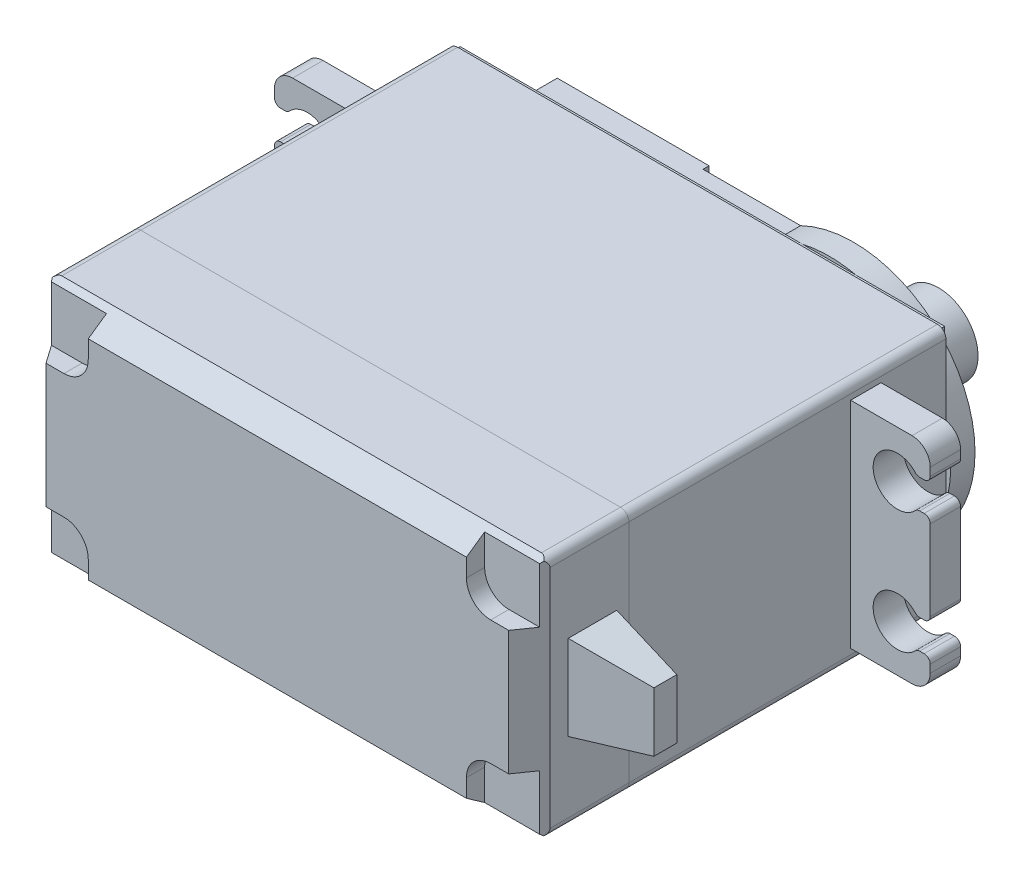
SolidWorks part; units mm, degrees
ref_plane "Front Plane" through (0, 0, 0) normal (0, 0, 1) x (1, 0, 0)
ref_plane "Top Plane" through (0, 0, 0) normal (0, 1, 0) x (1, 0, 0)
ref_plane "Right Plane" through (0, 0, 0) normal (1, 0, 0) x (0, 0, -1)
sketch "Sketch1" plane through (0, 0, 0) normal (0, 0, 1) x (1, 0, 0)
  line L1 (20.45, -10) -> (-20.45, -10)
  line L2 (20.45, -10) -> (20.45, 10)
  line L3 (20.45, 10) -> (-20.45, 10)
  line L4 (-20.45, -10) -> (-20.45, 10)
  line L5 (20.45, -10) -> (-20.45, 10) construction
  line L6 (20.45, 10) -> (-20.45, -10) construction
  point P0 (0, 0)
  dimension "D1" = 40.9
  dimension "D2" = 20
extrude "Boss-Extrude1" add sketch "Sketch1" along normal blind 19.3
sketch "Sketch3" plane through (0, 0, 0) normal (0, 0, -1) x (-1, 0, 0)
  line L4 (20.45, -10) -> (20.45, 10)
  line L5 (20.45, 10) -> (-20.45, 10)
  line L6 (-20.45, 10) -> (-20.45, -10)
  line L7 (-20.45, -10) -> (20.45, -10)
  line L8 (20.45, -10) -> (20.45, 10)
  line L9 (20.45, 10) -> (-20.45, 10)
  line L10 (-20.45, 10) -> (-20.45, -10)
  line L11 (-20.45, -10) -> (20.45, -10)
  dimension "D1" = 0
extrude "Boss-Extrude2" add sketch "Sketch3" along normal blind 6.8 separate body
sketch "Sketch4" plane through (0, 0, 19.3) normal (0, 0, 1) x (1, 0, 0)
  line L4 (-20.45, 10) -> (-20.45, -10)
  line L5 (-20.45, -10) -> (20.45, -10)
  line L6 (20.45, -10) -> (20.45, 10)
  line L7 (20.45, 10) -> (-20.45, 10)
  line L8 (-20.45, 10) -> (-20.45, -10)
  line L9 (-20.45, -10) -> (20.45, -10)
  line L10 (20.45, -10) -> (20.45, 10)
  line L11 (20.45, 10) -> (-20.45, 10)
  dimension "D1" = 0
extrude "Boss-Extrude3" add sketch "Sketch4" along normal blind 8.5 separate body
chamfer "Chamfer1" distance 2 angle 35 4 edges at (20.45, 0, 27.8) (0, -10, 27.8) (-20.45, 0, 27.8) (0, 10, 27.8)
sketch "Sketch5" plane through (0, 0, 27.8) normal (0, 0, 1) x (1, 0, 0)
  line L0 (-20.45, 10) -> (-19.0496, 8.5996) construction
  line L1 (-20.45, 10) -> (-15.57, 10)
  line L2 (-20.45, 10) -> (-20.45, 5.12)
  line L3 (-20.45, 5.12) -> (-17.57, 5.12)
  line L4 (-15.57, 10) -> (-15.57, 7.12)
  line L5 (-20.45, 10) -> (20.45, 10) construction
  line L6 (0, 10) -> (0, -11.6443) construction
  line L7 (0, 0) -> (20.45, 0) construction
  line L8 (20.45, 10) -> (20.45, -10) construction
  line L9 (20.45, 5.12) -> (17.57, 5.12)
  line L10 (15.57, 10) -> (15.57, 7.12)
  line L11 (20.45, 10) -> (15.57, 10)
  line L12 (20.45, 10) -> (20.45, 5.12)
  line L13 (-20.45, -5.12) -> (-17.57, -5.12)
  line L14 (-15.57, -10) -> (-15.57, -7.12)
  line L15 (-20.45, -10) -> (-15.57, -10)
  line L16 (-20.45, -10) -> (-20.45, -5.12)
  line L17 (20.45, -10) -> (20.45, -5.12)
  line L18 (20.45, -10) -> (15.57, -10)
  line L19 (15.57, -10) -> (15.57, -7.12)
  line L20 (20.45, -5.12) -> (17.57, -5.12)
  arc A0 (-17.57, 5.12) -> (-15.57, 7.12) centre (-17.57, 7.12) ccw
  arc A1 (17.57, 5.12) -> (15.57, 7.12) centre (17.57, 7.12) cw
  arc A2 (-17.57, -5.12) -> (-15.57, -7.12) centre (-17.57, -7.12) cw
  arc A3 (17.57, -5.12) -> (15.57, -7.12) centre (17.57, -7.12) ccw
  point P10 (-15.57, 5.12)
  dimension "D3" = 2
  dimension "D1" = 4.88
  dimension "D2" = 4.88
extrude "Cut-Extrude1" cut sketch "Sketch5" against normal blind 1.5
sketch "Sketch6" plane through (0, 0, -6.8) normal (0, 0, -1) x (-1, 0, 0)
  line L1 (19.95, -9.75) -> (-19.95, -9.75)
  line L2 (19.95, -9.75) -> (19.95, 9.75)
  line L3 (19.95, 9.75) -> (-19.95, 9.75)
  line L4 (-19.95, -9.75) -> (-19.95, 9.75)
  line L5 (19.95, -9.75) -> (-19.95, 9.75) construction
  line L6 (19.95, 9.75) -> (-19.95, -9.75) construction
  point P0 (0, 0)
  dimension "D1" = 0.25
  dimension "D2" = 0.5
extrude "Boss-Extrude4" add sketch "Sketch6" along normal blind 0.4
sketch "Sketch7" plane through (0, 0, -7.2) normal (0, 0, -1) x (-1, 0, 0)
  line L0 (-20.45, 0) -> (20.45, 0) construction
  line L1 (-20.45, 10) -> (-20.45, -10) construction
  line L2 (20.45, -10) -> (20.45, 10) construction
  line L3 (20.45, 10) -> (-20.45, 10) construction
  line L4 (-6.09, 10) -> (-6.09, -9.75) construction
  line L5 (-19.95, -9.75) -> (19.95, -9.75) construction
  line L6 (-6.09, 8.9995) -> (14.45, 8.9995)
  line L7 (14.45, 8.9995) -> (14.45, 3)
  line L8 (-6.09, -8.9995) -> (14.45, -8.9995)
  line L9 (14.45, -8.9995) -> (14.45, -3)
  arc A0 (-6.09, 8.9995) -> (-6.09, -8.9995) centre (-10.45, 0) ccw
  arc A1 (14.45, -3) -> (14.45, 3) centre (14.45, 0) ccw
  point P18 (17.45, 0)
  dimension "D1" = 14.36
  dimension "D2" = 6
  dimension "D3" = 3
extrude "Boss-Extrude5" add sketch "Sketch7" along normal blind 2
sketch "Sketch8" plane through (0, 0, -9.2) normal (0, 0, -1) x (-1, 0, 0)
  circle A0 centre (-10.45, 0) radius 6.5
  dimension "D1" = 13
extrude "Boss-Extrude6" add sketch "Sketch8" along normal blind 1.5
sketch "Sketch9" plane through (0, 0, -10.7) normal (0, 0, -1) x (-1, 0, 0)
  circle A0 centre (-10.45, 0) radius 5.5
  dimension "D1" = 11
extrude "Boss-Extrude8" add sketch "Sketch9" along normal blind 0.5
sketch "Sketch11" plane through (0, 0, -11.2) normal (0, 0, -1) x (-1, 0, 0)
  circle A0 centre (-10.45, 0) radius 3.25
  dimension "D1" = 6.5
extrude "Boss-Extrude9" add sketch "Sketch11" along normal blind 5
sketch "Sketch12" plane through (0, 0, -9.2) normal (0, 0, -1) x (-1, 0, 0)
  line L0 (-6.09, -8.9995) -> (14.45, -8.9995) construction
  line L1 (14.45, 8.9995) -> (1.95, 8.9995)
  line L2 (14.45, 8.9995) -> (14.45, -8.9995)
  line L3 (14.45, -8.9995) -> (1.95, -8.9995)
  line L4 (1.95, 8.9995) -> (1.95, 1.75)
  line L5 (2.95, 7.9995) -> (2.95, -7.9995)
  line L6 (13.45, -7.9995) -> (2.95, -7.9995)
  line L7 (13.45, 7.9995) -> (13.45, -7.9995)
  line L8 (13.45, 7.9995) -> (2.95, 7.9995)
  line L10 (1.95, -1.75) -> (1.95, -8.9995)
  line L12 (1.95, 8.9995) -> (1.95, -8.9995) construction
  arc A0 (1.95, 1.75) -> (1.95, -1.75) centre (1.95, 0) ccw
  dimension "D3" = 3.5
  dimension "D1" = 12.5
  dimension "D2" = 1
extrude "Boss-Extrude10" add sketch "Sketch12" along normal blind 0.5
fillet "Fillet1" radius 0.7 4 edges at (-20.45, -10, 9.65) (-20.45, 10, 9.65) (20.45, 10, 9.65) (20.45, -10, 9.65)
fillet "Fillet2" radius 0.7 4 edges at (-20.45, 10, -3.4) (-20.45, -10, -3.4) (20.45, -10, -3.4) (20.45, 10, -3.4)
fillet "Fillet3" radius 0.7 4 edges at (20.45, 10, 22.55) (-20.45, 10, 22.55) (-20.45, -10, 22.55) (20.45, -10, 22.55)
sketch "Sketch13" plane through (0, 0, -7.2) normal (0, 0, -1) x (-1, 0, 0)
  line L0 (20.45, 8.85) -> (25.5, 8.85)
  line L1 (20.45, -9.3) -> (20.45, 9.3) construction
  line L2 (27, 7.35) -> (27, 6.7)
  line L3 (0, 0) -> (27, 0) construction
  line L4 (19.75, 10) -> (-19.75, 10) construction
  line L5 (25.9, 8.85) -> (25.9, 0) construction
  line L6 (26.133, 6.2) -> (26.5, 6.2)
  line L7 (26.133, 3.8) -> (26.5, 3.8)
  line L8 (27, 3.3) -> (27, -3.3)
  line L9 (20.45, -8.85) -> (25.5, -8.85)
  line L10 (26.133, -3.8) -> (26.5, -3.8)
  line L11 (26.133, -6.2) -> (26.5, -6.2)
  line L12 (27, -7.35) -> (27, -6.7)
  line L13 (20.45, 8.85) -> (20.45, -8.85)
  arc A0 (25.7664, 6.36) -> (25.7664, 3.64) centre (24.3, 5) ccw
  arc A1 (25.7664, 3.64) -> (26.133, 3.8) centre (26.133, 3.3) cw
  arc A2 (25.7664, 6.36) -> (26.133, 6.2) centre (26.133, 6.7) ccw
  arc A3 (26.5, 3.8) -> (27, 3.3) centre (26.5, 3.3) cw
  arc A4 (26.5, 6.2) -> (27, 6.7) centre (26.5, 6.7) ccw
  arc A5 (25.5, 8.85) -> (27, 7.35) centre (25.5, 7.35) cw
  arc A6 (25.5, -8.85) -> (27, -7.35) centre (25.5, -7.35) ccw
  arc A7 (26.5, -6.2) -> (27, -6.7) centre (26.5, -6.7) cw
  arc A8 (26.5, -3.8) -> (27, -3.3) centre (26.5, -3.3) ccw
  arc A9 (25.7664, -6.36) -> (26.133, -6.2) centre (26.133, -6.7) cw
  arc A10 (25.7664, -3.64) -> (26.133, -3.8) centre (26.133, -3.3) ccw
  arc A11 (25.7664, -6.36) -> (25.7664, -3.64) centre (24.3, -5) cw
  point P18 (25.9, 3.8)
  point P21 (25.9, 6.2)
  point P24 (27, 3.8)
  point P29 (27, 8.85)
  point P47 (27, -8.85)
  point P48 (27, -3.8)
  point P49 (25.9, -6.2)
  point P50 (25.9, -3.8)
  dimension "D3" = 4
  dimension "D7" = 0.5
  dimension "D8" = 1.5
  dimension "D1" = 6.55
  dimension "D2" = 1.15
  dimension "D4" = 5
  dimension "D5" = 24.3
  dimension "D6" = 1.1
extrude "Boss-Extrude11" add sketch "Sketch13" against normal blind 2.5 from offset 5.74 offset against normal yes
mirror "Mirror1" about plane through (0, 0, 0) normal (1, 0, 0) of "Boss-Extrude11"
sketch "Sketch14" plane through (20.45, 0, 0) normal (1, 0, 0) x (0, 0, -1)
  line L0 (-27.8, -5.12) -> (-27.8, 5.12) construction
  line L1 (-24.3, 3.5) -> (-20.3, 3.5)
  line L2 (-24.3, 3.5) -> (-24.3, -3.5)
  line L3 (-24.3, -3.5) -> (-20.3, -3.5)
  line L4 (-20.3, 3.5) -> (-20.3, -3.5)
  line L5 (-24.3, 3.5) -> (-20.3, -3.5) construction
  line L6 (-24.3, -3.5) -> (-20.3, 3.5) construction
  point P0 (-22.3, 0)
  point P5 (0, 0)
  dimension "D1" = 4
  dimension "D2" = 7
  dimension "D3" = 3.5
extrude "Boss-Extrude12" add sketch "Sketch14" along normal blind 6 draft 10
